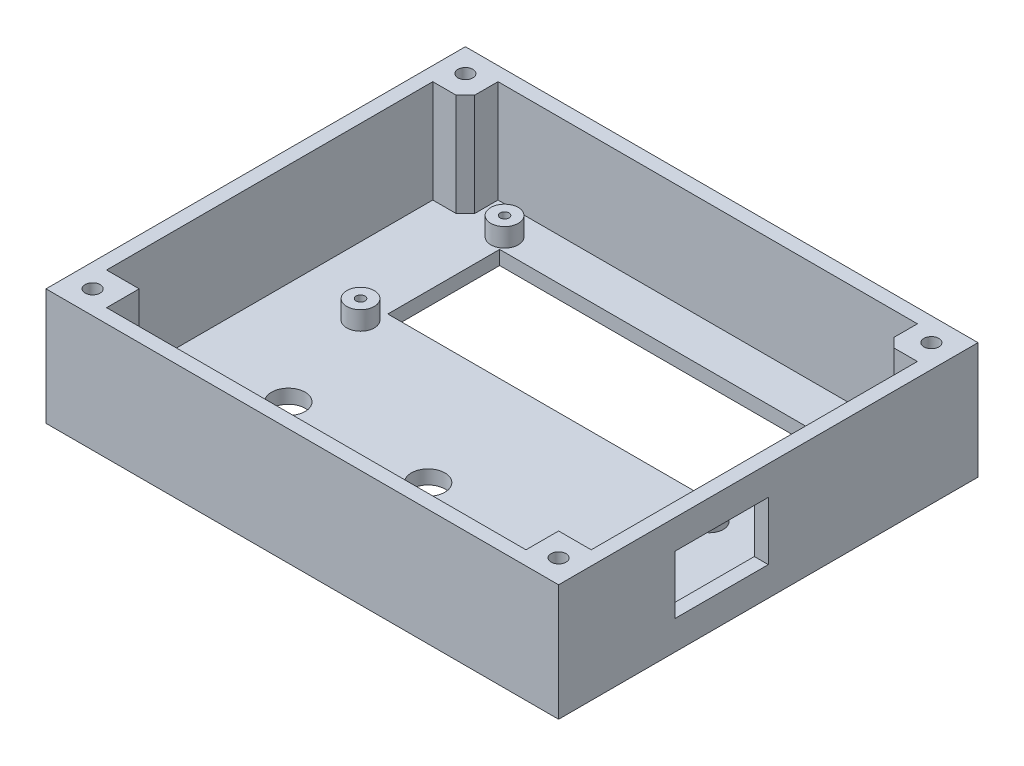
SolidWorks part; units mm, degrees
ref_plane "Alzado" through (0, 0, 0) normal (0, 0, 1) x (1, 0, 0)
ref_plane "Planta" through (0, 0, 0) normal (0, 1, 0) x (1, 0, 0)
ref_plane "Vista lateral" through (0, 0, 0) normal (1, 0, 0) x (0, 0, -1)
sketch "Croquis1" plane through (0, 0, 0) normal (0, 1, 0) x (1, 0, 0)
  line L0 (-55, 45) -> (55, 45)
  line L1 (-60, -50) -> (60, -50) construction
  line L2 (-60, -50) -> (-60, 50) construction
  line L3 (-60, 50) -> (60, 50) construction
  line L4 (60, -50) -> (60, 50) construction
  line L5 (-60, -50) -> (60, 50) construction
  line L6 (-60, 50) -> (60, -50) construction
  line L7 (55, -45) -> (55, 45)
  line L8 (-55, -45) -> (55, -45)
  line L9 (-55, -45) -> (-55, 45)
  point P0 (0, 0)
  dimension "D1" = 120
  dimension "D2" = 100
  dimension "D3" = 5
extrude "Saliente-Extruir1" add sketch "Croquis1" along normal blind 25
shell "Vaciado1" thickness 3
sketch "Croquis2" plane through (0, 3, 0) normal (0, 1, 0) x (1, 0, 0)
  line L0 (0, 42) -> (0, -42) construction
  line L1 (52, 42) -> (-52, 42) construction
  line L2 (-52, -42) -> (52, -42) construction
  line L4 (-35.65, 9) -> (35.65, 9)
  line L5 (-35.65, 9) -> (-35.65, 33)
  line L6 (-35.65, 33) -> (35.65, 33)
  line L7 (35.65, 9) -> (35.65, 33)
  line L8 (-35.65, 9) -> (35.65, 33) construction
  line L9 (-35.65, 33) -> (35.65, 9) construction
  point P6 (0, 21)
  dimension "D1" = 71.3
  dimension "D2" = 24
  dimension "D3" = 9
extrude "Cortar-Extruir1" cut sketch "Croquis2" against normal through all
sketch "Croquis4" plane through (0, 3, 0) normal (0, 1, 0) x (1, 0, 0)
  line L0 (35.65, 33) -> (-35.65, 33) construction
  line L1 (-40, 2.4) -> (40, 2.4) construction
  line L2 (-40, 2.4) -> (-40, 38.4) construction
  line L3 (-40, 38.4) -> (40, 38.4) construction
  line L4 (40, 2.4) -> (40, 38.4) construction
  line L5 (-40, 2.4) -> (40, 38.4) construction
  line L6 (-40, 38.4) -> (40, 2.4) construction
  line L7 (37.45, 4.95) -> (37.45, 3.5) construction
  line L8 (37.45, 4.95) -> (38.9, 4.95) construction
  circle A0 centre (37.45, 4.95) radius 1.45
  circle A1 centre (-37.45, 4.95) radius 1.45
  circle A2 centre (-37.45, 35.85) radius 1.45
  circle A3 centre (37.45, 35.85) radius 1.45
  circle A4 centre (-37.45, 35.85) radius 2.95
  circle A5 centre (-37.45, 4.95) radius 2.95
  circle A6 centre (37.45, 35.85) radius 2.95
  circle A7 centre (37.45, 4.95) radius 2.95
  point P0 (0, 20.4)
  dimension "D7" = 2.9
  dimension "D1" = 80
  dimension "D2" = 36
  dimension "D3" = 0
  dimension "D4" = 5.4
  dimension "D5" = 1.1
  dimension "D6" = 1.1
  dimension "D10" = 1.5
  dimension "D8" = 2
  dimension "D9" = 2
extrude "Saliente-Extruir2" add sketch "Croquis4" along normal blind 4
sketch "Croquis5" plane through (0, 7, 0) normal (0, 1, 0) x (1, 0, 0)
  circle A0 centre (-37.45, 35.85) radius 1.45 construction
  circle A1 centre (-37.45, 35.85) radius 1.45
  circle A2 centre (-37.45, 35.85) radius 0.95
  dimension "D1" = 0.5
extrude "Saliente-Extruir3" add sketch "Croquis5" against normal through all
pattern_linear "MatrizL1" count 2 spacing 74.9 along (1, 0, 0) count 2 spacing 30.9 along (0, 0, 1) of "Saliente-Extruir3"
sketch "Croquis6" plane through (0, 25, 0) normal (0, 1, 0) x (1, 0, 0)
  line L1 (-55, 45) -> (-45, 45)
  line L2 (-55, 45) -> (-55, 35)
  line L3 (-55, 35) -> (-45, 35)
  line L4 (-45, 45) -> (-45, 35)
  line L5 (-55, -45) -> (-45, -45)
  line L6 (-55, -45) -> (-55, -35)
  line L7 (-55, -35) -> (-45, -35)
  line L8 (-45, -45) -> (-45, -35)
  line L9 (55, -45) -> (45, -45)
  line L10 (55, -45) -> (55, -35)
  line L11 (55, -35) -> (45, -35)
  line L12 (45, -45) -> (45, -35)
  line L13 (55, 45) -> (45, 45)
  line L14 (55, 45) -> (55, 35)
  line L15 (55, 35) -> (45, 35)
  line L16 (45, 45) -> (45, 35)
  dimension "D1" = 10
  dimension "D2" = 10
  dimension "D3" = 10
  dimension "D4" = 10
  dimension "D5" = 10
  dimension "D6" = 10
  dimension "D7" = 10
  dimension "D8" = 10
extrude "Saliente-Extruir4" add sketch "Croquis6" against normal through all
sketch "Croquis7" plane through (0, 25, 0) normal (0, 1, 0) x (1, 0, 0)
  line L0 (-55, 45) -> (-45, 35) construction
  line L1 (45, 35) -> (55, 45) construction
  line L2 (55, -45) -> (45, -35) construction
  line L3 (-55, -45) -> (-45, -35) construction
  circle A0 centre (-50, -40) radius 1.6
  circle A1 centre (50, -40) radius 1.6
  circle A2 centre (50, 40) radius 1.6
  circle A3 centre (-50, 40) radius 1.6
  dimension "D1" = 3.2
  dimension "D2" = 3.2
  dimension "D3" = 3.2
  dimension "D4" = 3.2
extrude "Cortar-Extruir2" cut sketch "Croquis7" against normal through all
sketch "Croquis8" plane through (0, 0, 0) normal (0, -1, 0) x (1, 0, 0)
  circle A0 centre (50, -40) radius 3.1
  circle A1 centre (-50, -40) radius 3.1
  circle A2 centre (-50, 40) radius 3.1
  circle A3 centre (50, 40) radius 3.1
  dimension "D1" = 6.2
  dimension "D2" = 6.2
  dimension "D3" = 6.2
  dimension "D4" = 6.2
extrude "Cortar-Extruir3" cut sketch "Croquis8" against normal blind 4
chamfer "Chaflán1" distance 2 angle 45 2 edges at (45, 14, -35) (-45, 14, -35)
sketch "Croquis10" plane through (0, 0, 0) normal (0, -1, 0) x (1, 0, 0)
  line L0 (0, -9) -> (0, 45) construction
  line L1 (-35.65, -9) -> (35.65, -9) construction
  line L2 (-55, 45) -> (55, 45) construction
  circle A0 centre (0, 18) radius 3.6
  circle A1 centre (30, 18) radius 3.6
  circle A2 centre (-30, 18) radius 3.6
  dimension "D1" = 7.2
  dimension "D2" = 7.2
  dimension "D3" = 7.2
  dimension "D4" = 30
  dimension "D5" = 30
extrude "Cortar-Extruir5" cut sketch "Croquis10" against normal through all
sketch "Croquis11" plane through (55, 0, 0) normal (1, 0, 0) x (0, 0, -1)
  line L0 (45, 12.5) -> (-45, 12.5) construction
  line L1 (45, 25) -> (45, 0) construction
  line L2 (-45, 25) -> (-45, 0) construction
  line L4 (-20, 18.75) -> (0, 18.75)
  line L5 (-20, 18.75) -> (-20, 6.25)
  line L6 (-20, 6.25) -> (0, 6.25)
  line L7 (0, 18.75) -> (0, 6.25)
  line L8 (-20, 18.75) -> (0, 6.25) construction
  line L9 (-20, 6.25) -> (0, 18.75) construction
  point P6 (-10, 12.5)
  point P11 (0, 12.5)
  dimension "D1" = 12.5
  dimension "D2" = 20
  dimension "D3" = 45
extrude "Cortar-Extruir6" cut sketch "Croquis11" against normal blind 10
